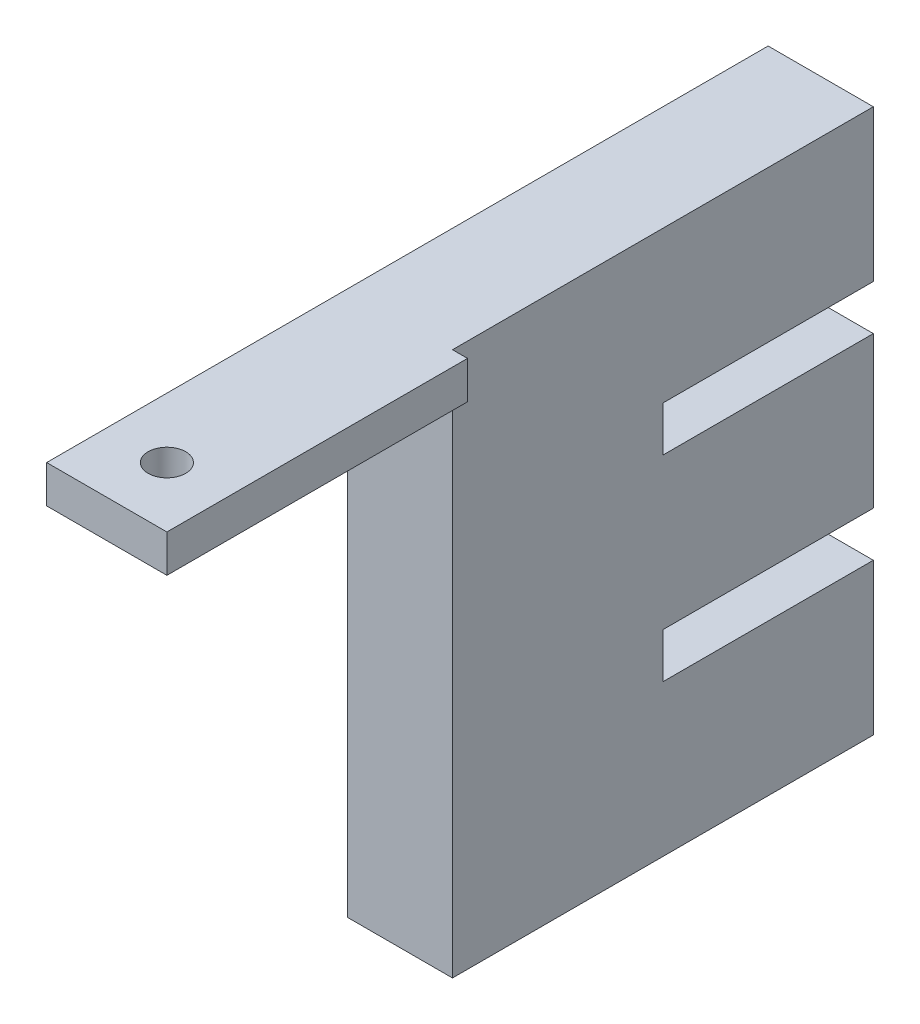
SolidWorks part; units mm, degrees
ref_plane "Front Plane" through (0, 0, 0) normal (0, 0, 1) x (1, 0, 0)
ref_plane "Top Plane" through (0, 0, 0) normal (0, 1, 0) x (1, 0, 0)
ref_plane "Right Plane" through (0, 0, 0) normal (1, 0, 0) x (0, 0, -1)
ref_plane "PZ_m16_000" through (0, 0, -16) normal (0, 0, 1) x (1, 0, 0)
sketch "S_box1" plane through (0, 0, -16) normal (0, 0, 1) x (1, 0, 0)
  line L0 (-4, 2) -> (4, 2)
  line L1 (4, 2) -> (4, 4.5)
  line L2 (4, 4.5) -> (-4, 4.5)
  line L3 (-4, 4.5) -> (-4, 2)
  dimension "P1" = 4
  dimension "P2" = 2
  dimension "P3" = 4
  dimension "P4" = 2
  dimension "P5" = 4
  dimension "P6" = 4.5
  dimension "P7" = 4
  dimension "P8" = 4.5
extrude "Boss_1" add sketch "S_box1" along normal blind 20
ref_plane "PZ_m44_000" through (0, 0, -44) normal (0, 0, 1) x (1, 0, 0)
sketch "S_box2" plane through (0, 0, -44) normal (0, 0, 1) x (1, 0, 0)
  line L0 (-4, -31.7) -> (3, -31.7)
  line L1 (3, -31.7) -> (3, 4.5)
  line L2 (3, 4.5) -> (-4, 4.5)
  line L3 (-4, 4.5) -> (-4, -31.7)
  dimension "P1" = 4
  dimension "P2" = 31.7
  dimension "P3" = 3
  dimension "P4" = 31.7
  dimension "P5" = 3
  dimension "P6" = 4.5
  dimension "P7" = 4
  dimension "P8" = 4.5
extrude "Boss_2" add sketch "S_box2" along normal blind 28
ref_plane "PY_p1_900" through (0, 1.9, 0) normal (0, 1, 0) x (1, 0, 0)
sketch "S_hole3" plane through (0, 1.9, 0) normal (0, 1, 0) x (1, 0, 0)
  circle A0 centre (0, 0) radius 1.25
  dimension "D1_S_hole3" = 2.5
extrude "Hole_3" cut sketch "S_hole3" along normal blind 2.7
ref_plane "PZ_m44_100" through (0, 0, -44.1) normal (0, 0, 1) x (1, 0, 0)
sketch "S_cut4" plane through (0, 0, -44.1) normal (0, 0, 1) x (1, 0, 0)
  line L0 (-4.1, -8.57) -> (3.1, -8.57)
  line L1 (3.1, -8.57) -> (3.1, -5.57)
  line L2 (3.1, -5.57) -> (-4.1, -5.57)
  line L3 (-4.1, -5.57) -> (-4.1, -8.57)
  dimension "P1" = 4.1
  dimension "P2" = 8.57
  dimension "P3" = 3.1
  dimension "P4" = 8.57
  dimension "P5" = 3.1
  dimension "P6" = 5.57
  dimension "P7" = 4.1
  dimension "P8" = 5.57
extrude "Pocket_4" cut sketch "S_cut4" along normal blind 14.1
sketch "S_cut5" plane through (0, 0, -44.1) normal (0, 0, 1) x (1, 0, 0)
  line L0 (-4.1, -21.63) -> (3.1, -21.63)
  line L1 (3.1, -21.63) -> (3.1, -18.63)
  line L2 (3.1, -18.63) -> (-4.1, -18.63)
  line L3 (-4.1, -18.63) -> (-4.1, -21.63)
  dimension "P1" = 4.1
  dimension "P2" = 21.63
  dimension "P3" = 3.1
  dimension "P4" = 21.63
  dimension "P5" = 3.1
  dimension "P6" = 18.63
  dimension "P7" = 4.1
  dimension "P8" = 18.63
extrude "Pocket_5" cut sketch "S_cut5" along normal blind 14.1
equation "\"plate_t\" = 3"
equation "\"clearance\" = 0.4"
